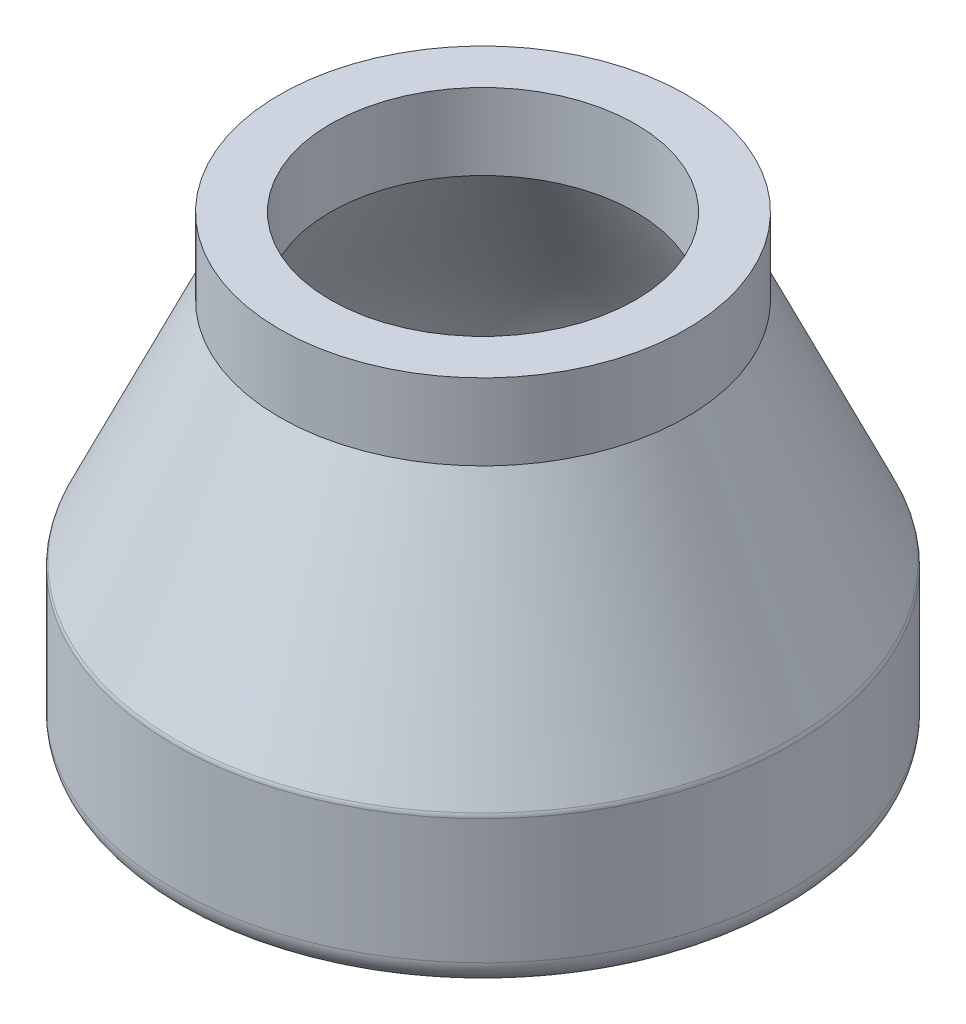
SolidWorks part; units mm, degrees
ref_plane "Płaszczyzna przednia" through (0, 0, 0) normal (0, 0, 1) x (1, 0, 0)
ref_plane "Płaszczyzna górna" through (0, 0, 0) normal (0, 1, 0) x (1, 0, 0)
ref_plane "Płaszczyzna prawa" through (0, 0, 0) normal (1, 0, 0) x (0, 0, -1)
sketch "Szkic1" plane through (0, 0, 0) normal (0, 1, 0) x (1, 0, 0)
  circle A0 centre (0, 0) radius 10.15
  dimension "D1" = 20.3
extrude "Wyciągnięcie-cienka ścianka1" add sketch "Szkic1" along normal blind 6 thin contours A0
fillet "Zaokrąglenie2" radius 1 1 edges at (12.15, 0, 0)
sketch "Szkic4" plane through (0, 0, 0) normal (1, 0, 0) x (0, 0, -1)
  line L0 (0, 0) -> (10.15, 0)
  line L1 (10.15, 0) -> (10.4, 6)
  line L2 (10.4, 6) -> (0, 6)
  line L3 (0, 6) -> (0, 0)
  line L6 (-10.15, 0) -> (10.15, 0) construction
  line L7 (10.15, 0) -> (10.15, 6) construction
  line L9 (10.15, 6) -> (-10.15, 6) construction
  dimension "D1" = 10.4
revolve "Wycięcie-obrót1" cut sketch "Szkic4" angle 360 about L3
sketch "Szkic5" plane through (0, 0, 0) normal (1, 0, 0) x (0, 0, -1)
  line L0 (0, 6) -> (12.15, 6)
  line L1 (12.15, 6) -> (8, 15)
  line L2 (8, 15) -> (0, 15)
  line L3 (0, 15) -> (0, 6)
  line L4 (12.15, 6) -> (-12.15, 6) construction
  spline S0 degree 3 poles (10.4, 6) (9.7775, 8.739) (8.5753, 10.4234) (6, 15) knots 0 0 0 0 1 1 1 1
  dimension "D2" = 9
  dimension "D3" = 8
  dimension "D4" = 2
revolve "Obrót1" add sketch "Szkic5" angle 360 about L3
fillet "Zaokrąglenie3" radius 0.4 2 edges at (12.15, 6, 0) (0, 6, 10.4)
sketch "Szkic6" plane through (0, 15, 0) normal (0, 1, 0) x (1, 0, 0)
  circle A0 centre (0, 0) radius 8
  circle A1 centre (0, 0) radius 6
  dimension "D1" = 12
  dimension "D2" = 16
extrude "Dodanie-wyciągnięcie1" add sketch "Szkic6" along normal blind 3
